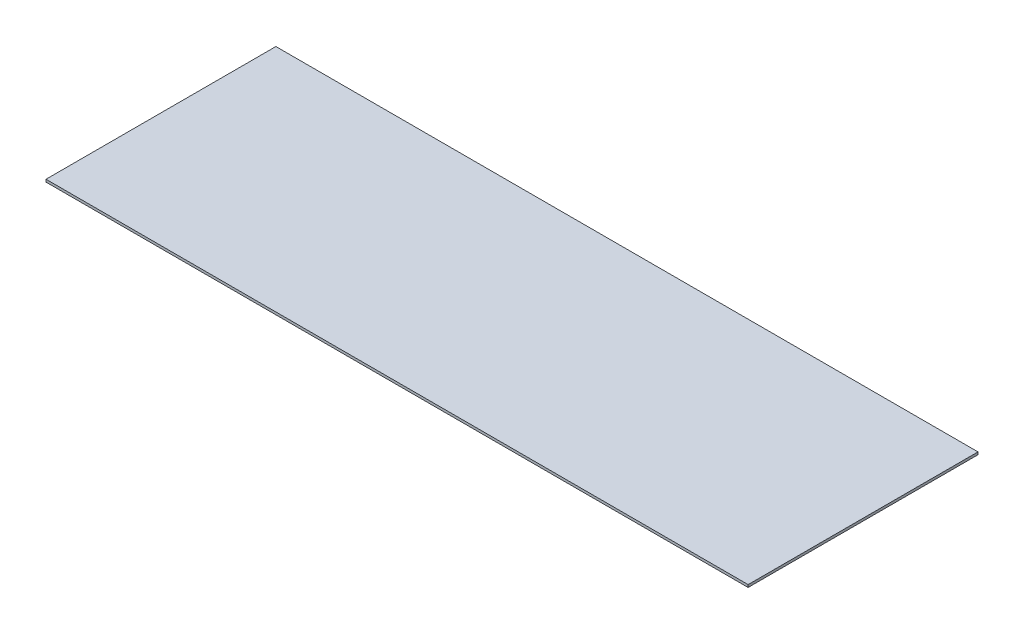
SolidWorks part; units mm, degrees
ref_plane "Front Plane" through (0, 0, 0) normal (0, 0, 1) x (1, 0, 0)
ref_plane "Top Plane" through (0, 0, 0) normal (0, 1, 0) x (1, 0, 0)
ref_plane "Right Plane" through (0, 0, 0) normal (1, 0, 0) x (0, 0, -1)
sketch "Sketch1" plane through (0, 0, 0) normal (0, 1, 0) x (1, 0, 0)
  line L1 (-446.0875, -146.05) -> (446.0875, -146.05)
  line L2 (-446.0875, -146.05) -> (-446.0875, 146.05)
  line L3 (-446.0875, 146.05) -> (446.0875, 146.05)
  line L4 (446.0875, -146.05) -> (446.0875, 146.05)
  line L5 (-446.0875, -146.05) -> (446.0875, 146.05) construction
  line L6 (-446.0875, 146.05) -> (446.0875, -146.05) construction
  point P0 (0, 0)
  dimension "D1" = 892.175
  dimension "D2" = 292.1
extrude "Boss-Extrude1" add sketch "Sketch1" along normal blind 3.175
